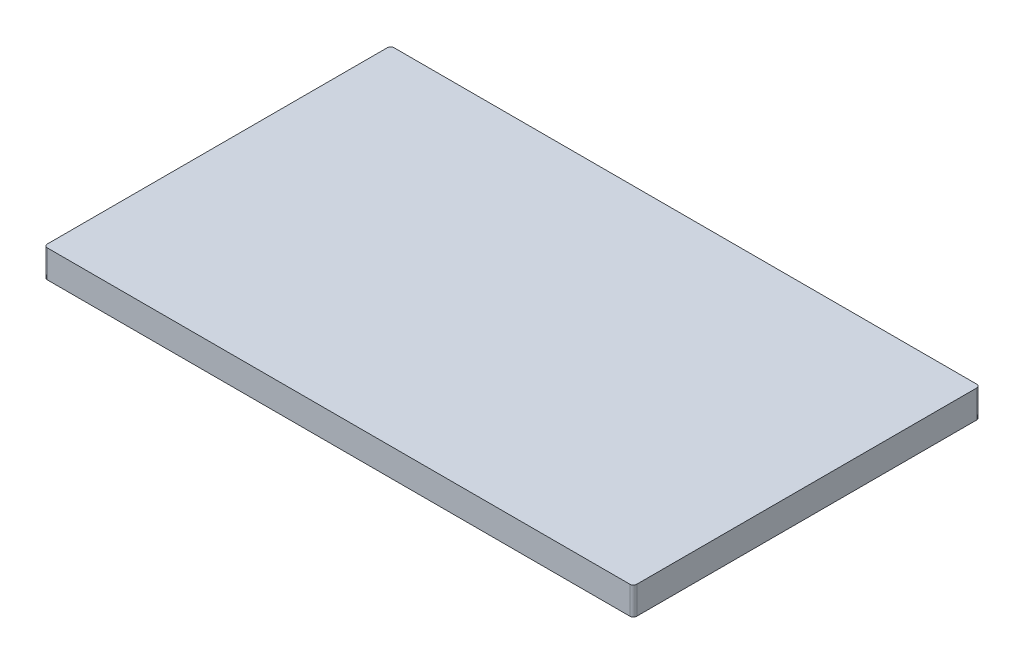
SolidWorks part; units mm, degrees
ref_plane "前视基准面" through (0, 0, 0) normal (0, 0, 1) x (1, 0, 0)
ref_plane "上视基准面" through (0, 0, 0) normal (0, 1, 0) x (1, 0, 0)
ref_plane "右视基准面" through (0, 0, 0) normal (1, 0, 0) x (0, 0, -1)
sketch "草图1" plane through (0, 0, 0) normal (0, 1, 0) x (1, 0, 0)
  line L1 (0, 0) -> (170, 0)
  line L2 (0, 0) -> (0, 100)
  line L3 (0, 100) -> (170, 100)
  line L4 (170, 0) -> (170, 100)
  dimension "D1" = 100
  dimension "D2" = 170
extrude "凸台-拉伸1" add sketch "草图1" along normal blind 8
fillet "圆角1" radius 1 4 edges at (0, 4, -100) (170, 4, -100) (170, 4, 0) (0, 4, 0)
